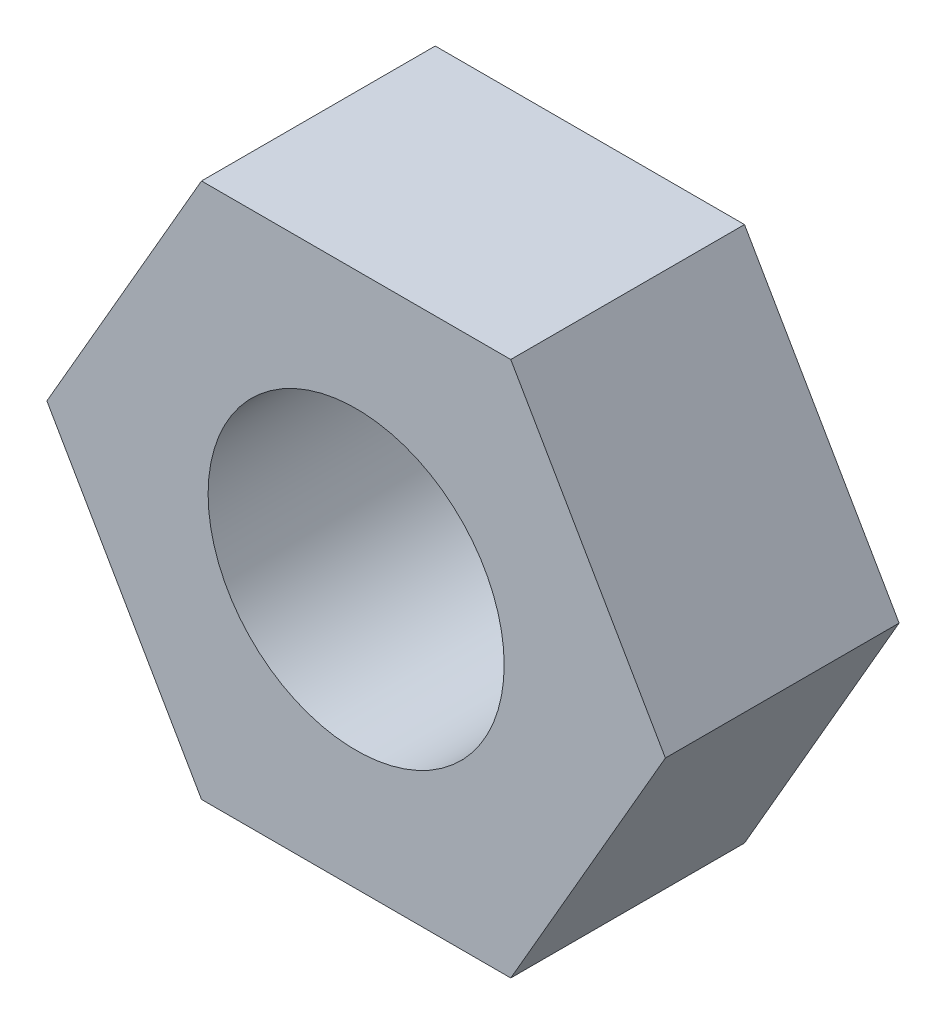
SolidWorks part; units mm, degrees
ref_plane "前视基准面" through (0, 0, 0) normal (0, 0, 1) x (1, 0, 0)
ref_plane "上视基准面" through (0, 0, 0) normal (0, 1, 0) x (1, 0, 0)
ref_plane "右视基准面" through (0, 0, 0) normal (1, 0, 0) x (0, 0, -1)
other "Configuration Table"
sketch "Sketch_Hex_blank" plane through (0, 0, 0) normal (0, 0, 1) x (1, 0, 0)
  line L0 (3.1754, 0) -> (1.5877, 2.75)
  line L1 (1.5877, 2.75) -> (-1.5877, 2.75)
  line L2 (-1.5877, 2.75) -> (-3.1754, 0)
  line L3 (-3.1754, 0) -> (-1.5877, -2.75)
  line L4 (-1.5877, -2.75) -> (1.5877, -2.75)
  line L5 (1.5877, -2.75) -> (3.1754, 0)
extrude "Hex_blank" add sketch "Sketch_Hex_blank" along normal blind 2.4 from offset 0
sketch "Sketch_Nominal_thread_envelope" plane through (0, 0, 0) normal (0, 0, 1) x (1, 0, 0)
  circle A0 centre (0, 0) radius 1.52
  dimension "D1" = 3.04
extrude "Nominal_thread_envelope" cut sketch "Sketch_Nominal_thread_envelope" along normal blind 4.4 from offset 1
